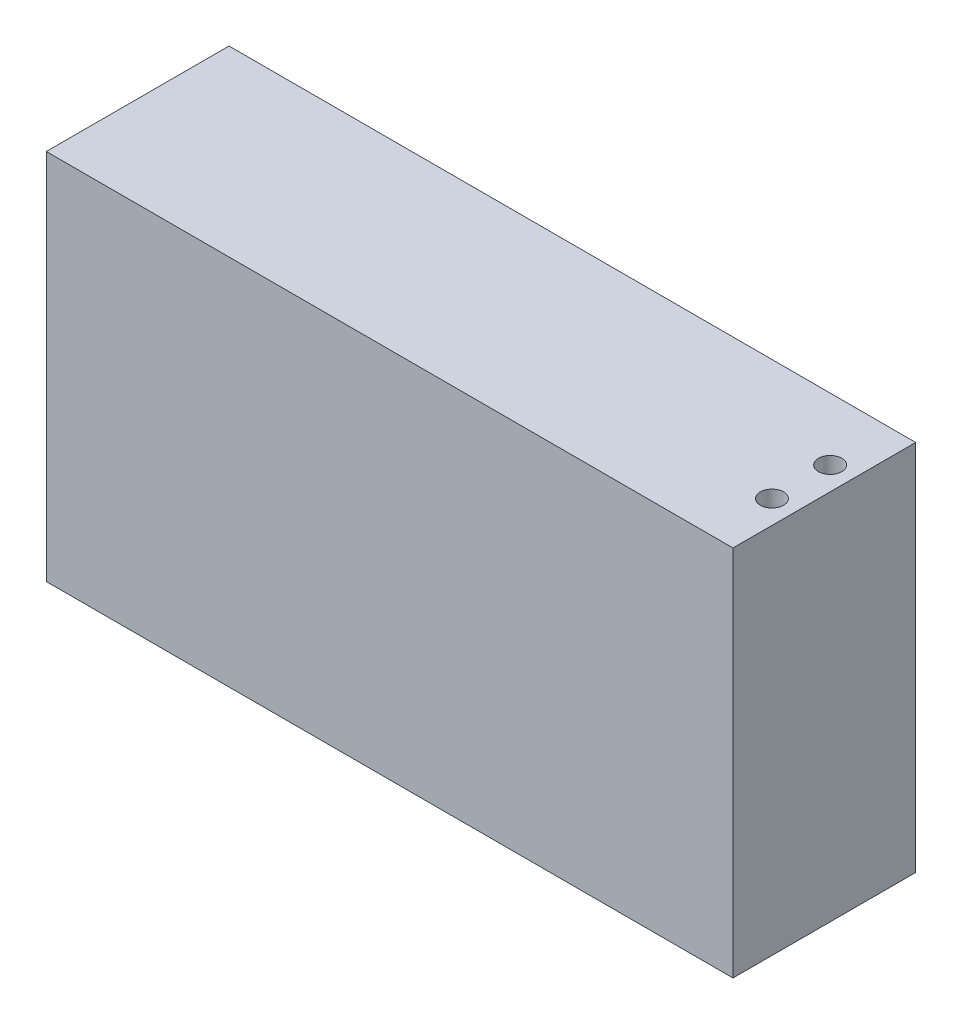
SolidWorks part; units mm, degrees
ref_plane "Front Plane" through (0, 0, 0) normal (0, 0, 1) x (1, 0, 0)
ref_plane "Top Plane" through (0, 0, 0) normal (0, 1, 0) x (1, 0, 0)
ref_plane "Right Plane" through (0, 0, 0) normal (1, 0, 0) x (0, 0, -1)
sketch "Sketch1" plane through (0, 0, 0) normal (0, 1, 0) x (1, 0, 0)
  line L1 (0, 0) -> (590, 0)
  line L2 (0, 0) -> (0, 157)
  line L3 (0, 157) -> (590, 157)
  line L4 (590, 0) -> (590, 157)
  dimension "D1" = 590
  dimension "D2" = 157
extrude "Boss-Extrude1" add sketch "Sketch1" along normal blind 320 contours L3 L4 L1 L2
sketch "Sketch2" plane through (0, 320, 0) normal (0, 1, 0) x (1, 0, 0)
  line L0 (570, 53.5) -> (570, 104.9998) construction
  line L1 (590, 0) -> (590, 157) construction
  line L2 (590, 78.5) -> (536.1712, 78.5) construction
  circle A0 centre (570, 103.5) radius 10
  circle A1 centre (570, 53.5) radius 10
  point P9 (0, 0)
  dimension "D2" = 20
  dimension "D3" = 20
  dimension "D1" = 50
  dimension "D4" = 20
extrude "Cut-Extrude1" cut sketch "Sketch2" against normal blind 80
